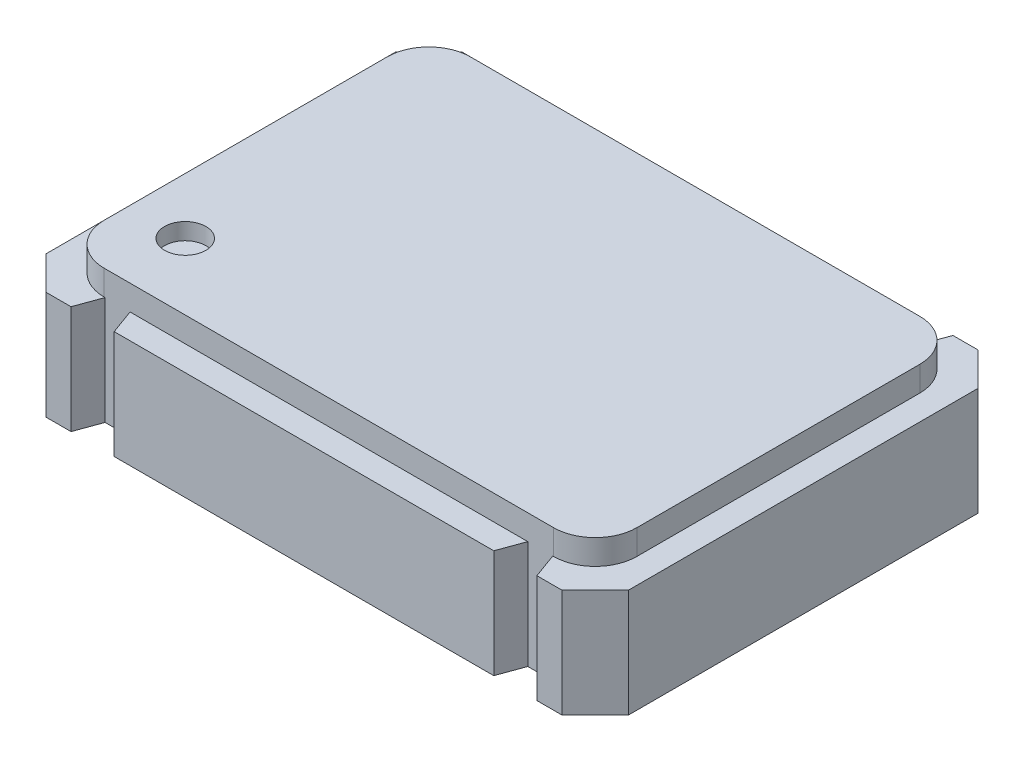
SolidWorks part; units mm, degrees
ref_plane "Front Plane" through (0, 0, 0) normal (0, 0, 1) x (1, 0, 0)
ref_plane "Top Plane" through (0, 0, 0) normal (0, 1, 0) x (1, 0, 0)
ref_plane "Right Plane" through (0, 0, 0) normal (1, 0, 0) x (0, 0, -1)
ref_plane "Plane1" through (0, 1.3, 0) normal (0, 1, 0) x (1, 0, 0)
sketch "Sketch1" plane through (0, 1.3, 0) normal (0, 1, 0) x (1, 0, 0)
  line L0 (3.5, 2.1) -> (0, 5.6)
  line L1 (0, 5.6) -> (-3.5, 2.1)
  line L2 (-3.5, 2.1) -> (-3.5, -2.1)
  line L3 (-3.5, -2.1) -> (0, -5.6)
  line L4 (0, -5.6) -> (3.5, -2.1)
  line L5 (3.5, -2.1) -> (3.5, 2.1)
extrude "Boss-Extrude1" add sketch "Sketch1" against normal blind 1.3
sketch "Sketch2" plane through (0, 0, 0) normal (0, -1, 0) x (1, 0, 0)
  line L0 (0, -5.6) -> (2.69, -2.91)
  line L1 (2.69, -2.91) -> (2.69, -2.2)
  line L2 (2.69, -2.2) -> (-2.69, -2.2)
  line L3 (-2.69, -2.2) -> (-2.69, -2.91)
  line L4 (-2.69, -2.91) -> (0, -5.6)
extrude "Cut-Extrude1" cut sketch "Sketch2" against normal through all
sketch "Sketch3" plane through (0, 0, 0) normal (0, -1, 0) x (1, 0, 0)
  line L0 (2.69, 2.2) -> (2.69, 2.91)
  line L1 (2.69, 2.91) -> (0, 5.6)
  line L2 (0, 5.6) -> (-2.69, 2.91)
  line L3 (-2.69, 2.91) -> (-2.69, 2.2)
  line L4 (-2.69, 2.2) -> (2.69, 2.2)
extrude "Cut-Extrude2" cut sketch "Sketch3" against normal through all
sketch "Sketch4" plane through (0, 1.3, 0) normal (0, 1, 0) x (-1, 0, 0)
  line L0 (-3.2, -2.2) -> (-3.2, 2.2)
  line L1 (-3.2, 2.2) -> (3.2, 2.2)
  line L2 (3.2, 2.2) -> (3.2, -2.2)
  line L3 (3.2, -2.2) -> (-3.2, -2.2)
extrude "Boss-Extrude2" add sketch "Sketch4" along normal blind 0.3
sketch "Sketch5" plane through (0, 0, 2.2) normal (0, 0, 1) x (1, 0, 0)
  line L0 (2.39, 0) -> (-2.39, 0)
  line L1 (-2.39, 0) -> (-2.39, 1.3)
  line L2 (-2.39, 1.3) -> (2.39, 1.3)
  line L3 (2.39, 1.3) -> (2.39, 0)
extrude "Boss-Extrude3" add sketch "Sketch5" along normal blind 0.3
sketch "Sketch6" plane through (0, 0, -2.2) normal (0, 0, -1) x (-1, 0, 0)
  line L0 (2.39, 0) -> (-2.39, 0)
  line L1 (-2.39, 0) -> (-2.39, 1.3)
  line L2 (-2.39, 1.3) -> (2.39, 1.3)
  line L3 (2.39, 1.3) -> (2.39, 0)
extrude "Boss-Extrude4" add sketch "Sketch6" along normal blind 0.3
draft "Draft1" type of draft neutral plane draft angle 20 faces to draft 4 face at (-2.69, 0.8125, -2.4663) face at (-2.39, 0.65, -2.35) face at (2.39, 0.65, -2.35) face at (2.69, 0.8125, -2.6438) neutral plane through (2.69, 1.3, -2.2) neutral plane normal (0, 0, -1) parameters "D1"=20
draft "Draft2" type of draft neutral plane draft angle 20 faces to draft 4 face at (2.69, 0.8125, 2.4663) face at (2.39, 0.65, 2.35) face at (-2.39, 0.65, 2.35) face at (-2.69, 0.8125, 2.6438) neutral plane through (-2.69, 1.3, 2.2) neutral plane normal (0, 0, 1) parameters "D1"=20
hole_wizard "Hole1" positions "Sketch8" profile "Sketch7" legacy
sketch "Sketch8" plane through (0, 1.6, 0) normal (0, 1, 0) x (1, 0, 0)
  point P0 (-2.524, -1.4031)
sketch "Sketch7" plane through (-2.524, 1.6, 1.4031) normal (1, 0, 0) x (0, 0, 1)
  line L0 (0, 0) -> (0, 0.2)
  line L1 (0, 0.2) -> (0.2488, 0.2)
  line L2 (0.2488, 0.2) -> (0.2488, 0)
  line L3 (0.2488, 0) -> (0, 0)
  line L4 (0, 110) -> (0, -10) construction
  dimension "Diameter" = 0.4975
  dimension "Depth" = 0.2
chamfer "Chamfer1" distance 0.2347 angle 70 2 edges at (2.8795, 0.65, 2.7205) (-2.8795, 0.65, -2.7205)
chamfer "Chamfer2" distance 0.3119 angle 45 2 edges at (2.8795, 0.65, -2.7205) (-2.8795, 0.65, 2.7205)
fillet "Fillet1" radius 0.5 4 edges at (3.2, 1.45, -2.2) (-3.2, 1.45, -2.2) (3.2, 1.45, 2.2) (-3.2, 1.45, 2.2)
